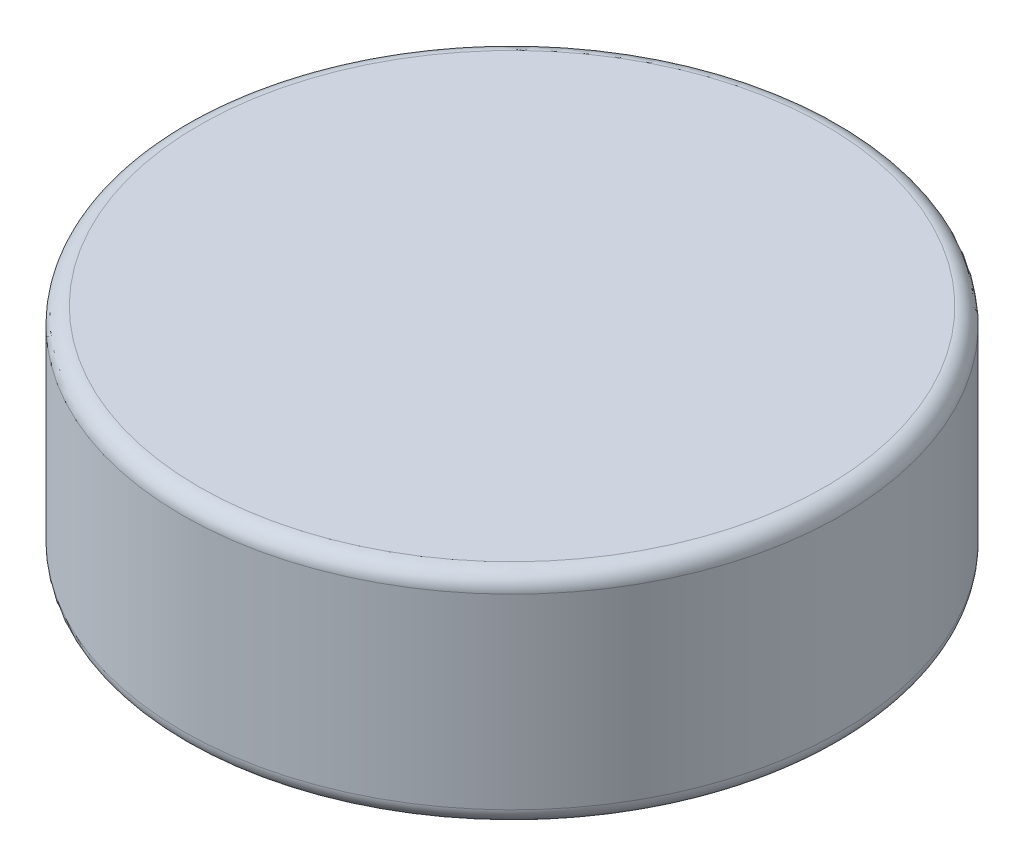
SolidWorks part; units mm, degrees
ref_plane "Ebene vorne" through (0, 0, 0) normal (0, 0, 1) x (1, 0, 0)
ref_plane "Ebene oben" through (0, 0, 0) normal (0, 1, 0) x (1, 0, 0)
ref_plane "Ebene rechts" through (0, 0, 0) normal (1, 0, 0) x (0, 0, -1)
sketch "Skizze1" plane through (0, 0, 0) normal (0, 1, 0) x (1, 0, 0)
  circle A0 centre (0, 0) radius 3
  dimension "D1" = 6
extrude "Aufsatz-Linear austragen1" add sketch "Skizze1" along normal blind 2
fillet "Verrundung1" radius 0.15 2 edges at (0, 0, 3) (0, 2, 3)
